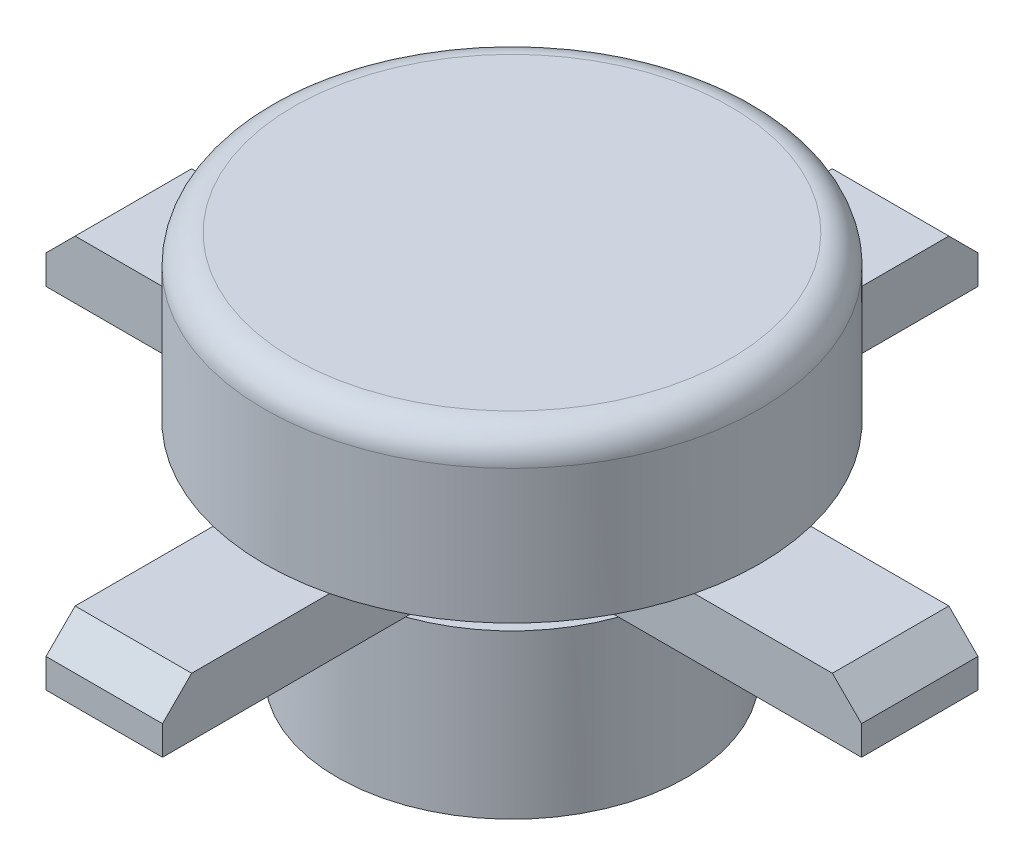
SolidWorks part; units mm, degrees
ref_plane "前视基准面" through (0, 0, 0) normal (0, 0, 1) x (1, 0, 0)
ref_plane "上视基准面" through (0, 0, 0) normal (0, 1, 0) x (1, 0, 0)
ref_plane "右视基准面" through (0, 0, 0) normal (1, 0, 0) x (0, 0, -1)
sketch "草图1" plane through (0, 0, 0) normal (0, 1, 0) x (1, 0, 0)
  circle A0 centre (0, 0) radius 4.25
  dimension "D1" = 8.5
extrude "凸台-拉伸1" add sketch "草图1" along normal blind 2.8
fillet "圆角1" radius 0.5 1 edges at (0, 2.8, 4.25)
sketch "草图2" plane through (0, 0, 0) normal (0, -1, 0) x (1, 0, 0)
  line L1 (-7, 1) -> (7, 1)
  line L2 (-7, 1) -> (-7, -1)
  line L3 (-7, -1) -> (7, -1)
  line L4 (7, 1) -> (7, -1)
  line L5 (-7, 1) -> (7, -1) construction
  line L6 (-7, -1) -> (7, 1) construction
  circle A0 centre (0, 0) radius 4.25 construction
  point P6 (0, 0)
  dimension "D1" = 2
  dimension "D2" = 14
extrude "凸台-拉伸2" add sketch "草图2" along normal blind 1
sketch "草图3" plane through (0, 0, 0) normal (0, -1, 0) x (1, 0, 0)
  line L1 (-1, 7) -> (1, 7)
  line L2 (-1, 7) -> (-1, -7)
  line L3 (-1, -7) -> (1, -7)
  line L4 (1, 7) -> (1, -7)
  line L5 (-1, 7) -> (1, -7) construction
  line L6 (-1, -7) -> (1, 7) construction
  arc A0 (4.1307, 1) -> (-4.1307, 1) centre (0, 0) ccw construction
  point P7 (0, 0)
  dimension "D1" = 14
  dimension "D2" = 2
extrude "凸台-拉伸3" add sketch "草图3" along normal blind 1
chamfer "倒角1" distance 0.5 angle 45 1 edges at (0, 0, 7)
chamfer "倒角2" distance 0.5 angle 45 1 edges at (7, 0, 0)
chamfer "倒角3" distance 0.5 angle 45 2 edges at (-7, 0, 0) (0, 0, -7)
sketch "草图4" plane through (0, -1, 0) normal (0, -1, 0) x (1, 0, 0)
  line L0 (7, -1) -> (7, 1) construction
  line L1 (1, 7) -> (-1, 7) construction
  circle A0 centre (0, 0) radius 3
  point P4 (7, 0)
  point P7 (0, 7)
  dimension "D1" = 6
extrude "凸台-拉伸4" add sketch "草图4" along normal blind 2.8
